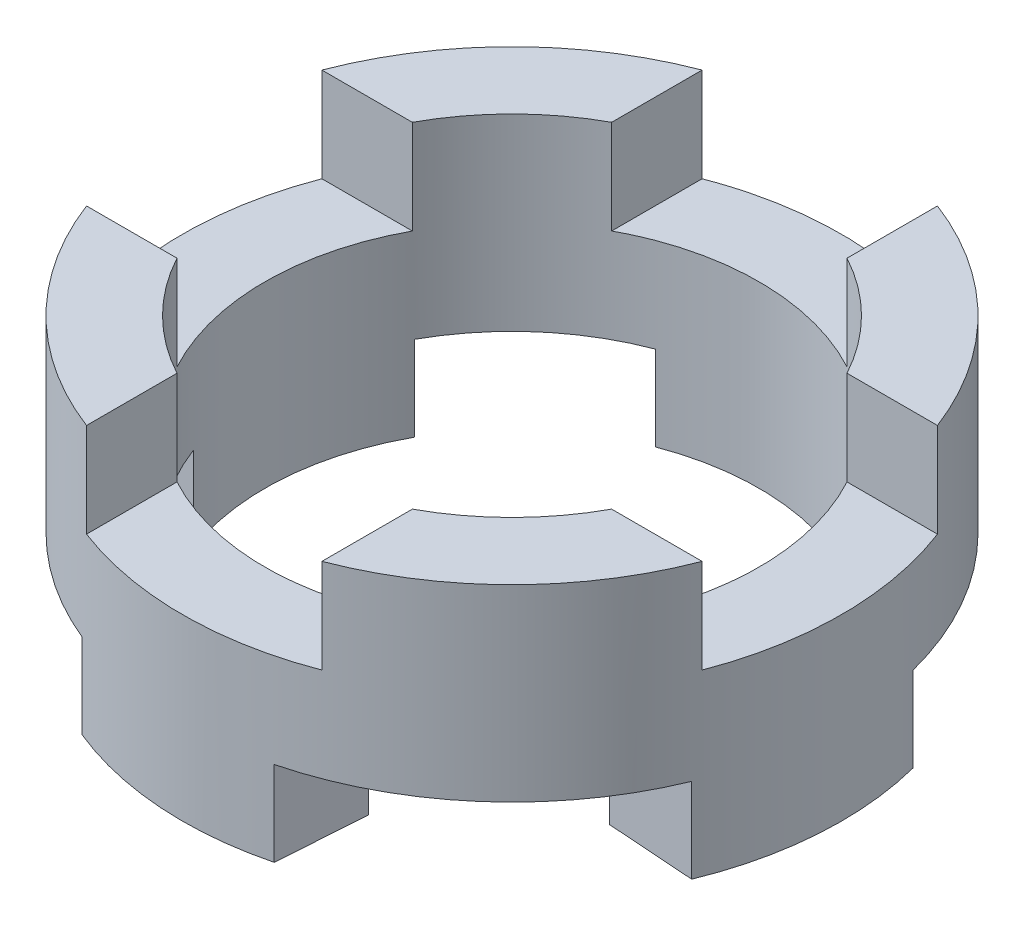
SolidWorks part; units mm, degrees
ref_plane "前视基准面" through (0, 0, 0) normal (0, 0, 1) x (1, 0, 0)
ref_plane "上视基准面" through (0, 0, 0) normal (0, 1, 0) x (1, 0, 0)
ref_plane "右视基准面" through (0, 0, 0) normal (1, 0, 0) x (0, 0, -1)
other "Configuration Table"
sketch "草图1" plane through (0, 0, 0) normal (0, 1, 0) x (1, 0, 0)
  circle A0 centre (0, 0) radius 5.25
  circle A1 centre (0, 0) radius 7
  dimension "D1" = 10.5
  dimension "D2" = 14
extrude "凸台-拉伸1" add sketch "草图1" along normal blind 4
sketch "草图2" plane through (0, 4, 0) normal (0, 1, 0) x (1, 0, 0)
  line L0 (0.3396, 0) -> (5.5896, 0) construction
  line L1 (0, -5.3859) -> (0, 5.1141) construction
  line L2 (-2.5, 2.5) -> (-2.5, 8)
  line L3 (-2.5, 8) -> (2.5, 8)
  line L4 (2.5, 8) -> (2.5, 2.5)
  line L5 (2.5, 2.5) -> (8, 2.5)
  line L6 (8, 2.5) -> (8, -2.5)
  line L7 (8, -2.5) -> (2.5, -2.5)
  line L8 (2.5, -2.5) -> (2.5, -8)
  line L9 (2.5, -8) -> (-2.5, -8)
  line L10 (-2.5, -8) -> (-2.5, -2.5)
  line L11 (-2.5, -2.5) -> (-8, -2.5)
  line L12 (-8, -2.5) -> (-8, 2.5)
  line L13 (-8, 2.5) -> (-2.5, 2.5)
  dimension "D1" = 2.5
  dimension "D2" = 2.5
  dimension "D3" = 2.5
  dimension "D4" = 2.5
  dimension "D5" = 2.5
  dimension "D6" = 2.5
  dimension "D7" = 2.5
  dimension "D8" = 2.5
  dimension "D9" = 8
  dimension "D10" = 8
  dimension "D11" = 8
  dimension "D12" = 8
extrude "切除-拉伸1" cut sketch "草图2" against normal blind 2
sketch "草图3" plane through (0, 0, 0) normal (0, -1, 0) x (1, 0, 0)
  line L0 (0, 0) -> (5.25, 0) construction
  line L1 (0, 0) -> (0, 5.25) construction
  line L2 (0, 0) -> (-0.1369, 1.9579) construction
  line L3 (0, 0) -> (1.8112, 0.1266) construction
  line L16 (-2.7527, 7.827) -> (-2.3481, 2.0412)
  line L17 (-2.3481, 2.0412) -> (-8.134, 1.6366)
  line L18 (-8.134, 1.6366) -> (-7.827, -2.7527)
  line L19 (-7.827, -2.7527) -> (-2.0412, -2.3481)
  line L20 (-2.0412, -2.3481) -> (-1.6366, -8.134)
  line L21 (-1.6366, -8.134) -> (2.7527, -7.827)
  line L22 (2.7527, -7.827) -> (2.3481, -2.0412)
  line L23 (2.3481, -2.0412) -> (8.134, -1.6366)
  line L24 (8.134, -1.6366) -> (7.827, 2.7527)
  line L25 (7.827, 2.7527) -> (2.0412, 2.3481)
  line L26 (2.0412, 2.3481) -> (1.6366, 8.134)
  line L27 (1.6366, 8.134) -> (-2.7527, 7.827)
  circle M22 centre (0, 0) radius 7
  circle M23 centre (0, 0) radius 5.25
  dimension "D1" = 4
  dimension "D2" = 90
  dimension "D3" = 2.2
  dimension "D4" = 2.2
  dimension "D5" = 2.2
  dimension "D6" = 2.2
  dimension "D7" = 2.2
  dimension "D8" = 2.2
  dimension "D9" = 2.2
  dimension "D10" = 2.2
  dimension "D11" = 8
  dimension "D12" = 8
  dimension "D13" = 8
  dimension "D14" = 8
extrude "凸台-拉伸2" add sketch "草图3" along normal blind 1.8 contours L26 L16 M23 M22 | L19 L17 M22 M23 | L22 L20 M22 M23 | L25 L23 M22 M23
